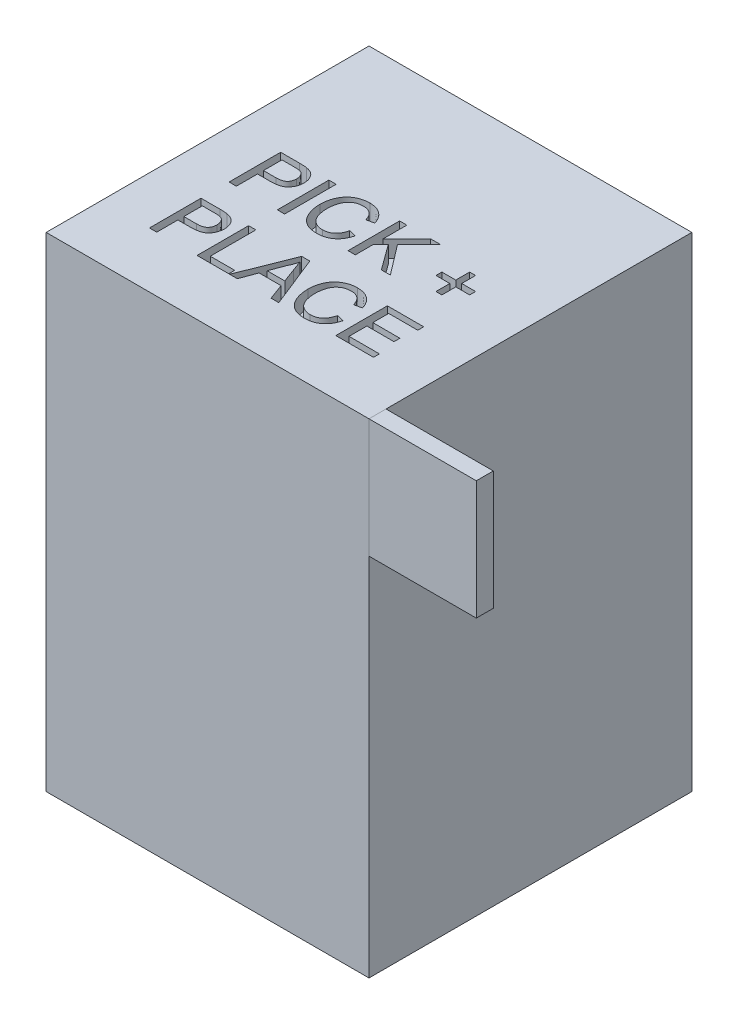
SolidWorks part; units mm, degrees
ref_plane "Front" through (0, 0, 0) normal (0, 0, 1) x (1, 0, 0)
ref_plane "Top" through (0, 0, 0) normal (0, 1, 0) x (1, 0, 0)
ref_plane "Right" through (0, 0, 0) normal (1, 0, 0) x (0, 0, -1)
sketch "Sketch1" plane through (0, 0, 0) normal (0, 1, 0) x (1, 0, 0)
  line L1 (-482.6, 482.6) -> (482.6, 482.6)
  line L2 (-482.6, 482.6) -> (-482.6, -482.6)
  line L3 (-482.6, -482.6) -> (482.6, -482.6)
  line L4 (482.6, 482.6) -> (482.6, -482.6)
  line L5 (-482.6, 482.6) -> (482.6, -482.6) construction
  line L6 (-482.6, -482.6) -> (482.6, 482.6) construction
  point P0 (0, 0)
  dimension "D1" = 965.2
extrude "Boss-Extrude1" add sketch "Sketch1" along normal blind 1447.8
sketch "Sketch2" plane through (0, 1447.8, 0) normal (0, 1, 0) x (1, 0, 0)
  line L0 (-357.4084, -78.6245) -> (395.5374, -78.6245) construction
  text T0 "PICK + \r\nPLACE" font "Arial" height in points 600
extrude "Cut-Extrude1" cut sketch "Sketch2" against normal blind 50.8
sketch "Sketch3" plane through (482.6, 0, 0) normal (1, 0, 0) x (0, 0, -1)
  line L0 (-482.6, 1447.8) -> (482.6, 1447.8) construction
  line L1 (-431.8, 1447.8) -> (-482.6, 1447.8)
  line L2 (-431.8, 1447.8) -> (-431.8, 1092.2)
  line L3 (-431.8, 1092.2) -> (-482.6, 1092.2)
  line L4 (-482.6, 1447.8) -> (-482.6, 1092.2)
  line L5 (-482.6, 1447.8) -> (-482.6, 0) construction
  dimension "D1" = 355.6
  dimension "D2" = 50.8
extrude "Boss-Extrude2" add sketch "Sketch3" along normal blind 320.802 separate body
